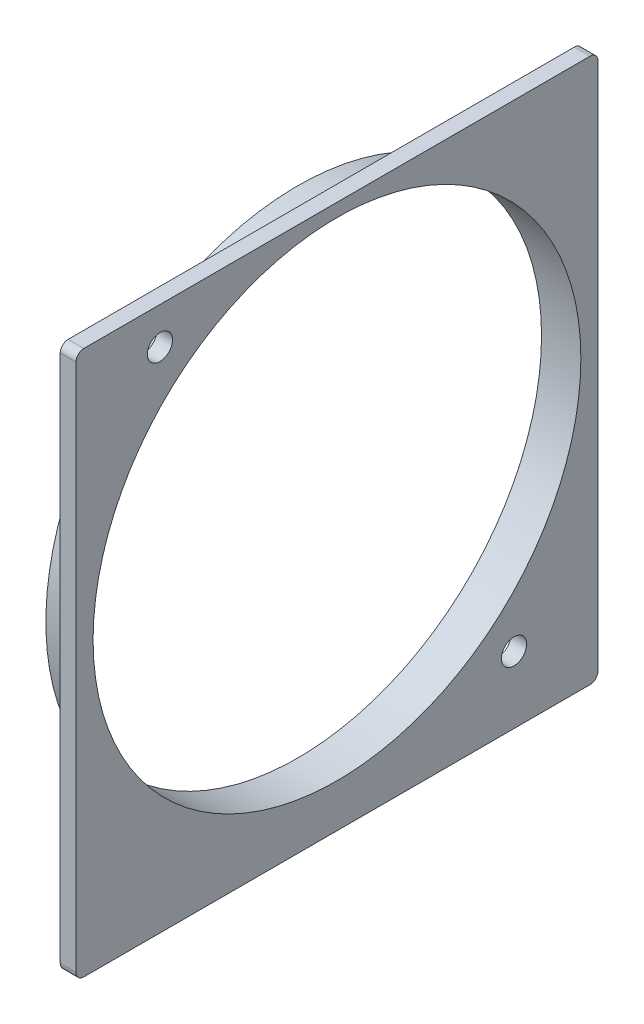
SolidWorks part; units mm, degrees
ref_plane "Front Plane" through (0, 0, 0) normal (0, 0, 1) x (1, 0, 0)
ref_plane "Top Plane" through (0, 0, 0) normal (0, 1, 0) x (1, 0, 0)
ref_plane "Right Plane" through (0, 0, 0) normal (1, 0, 0) x (0, 0, -1)
sketch "Sketch1" plane through (0, 0, 0) normal (1, 0, 0) x (0, 0, -1)
  line L1 (-33.175, -34.59) -> (33.175, -34.59)
  line L2 (-33.175, -34.59) -> (-33.175, 34.59)
  line L3 (-33.175, 34.59) -> (33.175, 34.59)
  line L4 (33.175, -34.59) -> (33.175, 34.59)
  line L5 (-33.175, -34.59) -> (33.175, 34.59) construction
  line L6 (-33.175, 34.59) -> (33.175, -34.59) construction
  point P0 (0, 0)
  dimension "D1" = 66.35
  dimension "D2" = 69.18
extrude "Boss-Extrude1" add sketch "Sketch1" along normal blind 2
sketch "Sketch2" plane through (0, 0, 0) normal (-1, 0, 0) x (0, 0, 1)
  line L0 (33.175, -34.59) -> (-33.175, -34.59) construction
  circle A0 centre (0, 1.91) radius 31
  dimension "D1" = 62
  dimension "D2" = 36.5
extrude "Cut-Extrude1" cut sketch "Sketch2" against normal through all
sketch "Sketch3" plane through (2, 0, 0) normal (1, 0, 0) x (0, 0, -1)
  line L1 (-22.5, -26.09) -> (22.5, -26.09) construction
  line L2 (-22.5, -26.09) -> (-22.5, 29.91) construction
  line L3 (-22.5, 29.91) -> (22.5, 29.91) construction
  line L4 (22.5, -26.09) -> (22.5, 29.91) construction
  line L5 (-22.5, -26.09) -> (22.5, 29.91) construction
  line L6 (-22.5, 29.91) -> (22.5, -26.09) construction
  point P0 (0, 1.91)
  dimension "D1" = 28
  dimension "D2" = 45
hole_wizard "M3 Clearance Hole1" positions "Sketch4" profile "Sketch5" hole size "M3" standard "ANSI Metric" end condition through all
sketch "Sketch4" plane through (2, 0, 0) normal (1, 0, 0) x (0, 0, -1)
  point P0 (-22.5, 29.91)
  point P3 (22.5, -26.09)
sketch "Sketch5" plane through (2, 29.91, 22.5) normal (0, 1, 0) x (0, 0, -1)
  line L0 (0, 0) -> (0, 2)
  line L1 (0, 2) -> (1.6, 2)
  line L2 (1.6, 2) -> (1.6, 0)
  line L5 (1.6, 0) -> (0, 0)
  line L11 (0, -6.35) -> (0, 107.95) construction
  dimension "Thru Hole Dia." = 3.2
  dimension "Thru Hole Depth" = 2
sketch "Sketch6" plane through (0, 0, 0) normal (1, 0, 0) x (0, 0, -1)
  circle A0 centre (0, 1.91) radius 31 construction
  circle A1 centre (0, 1.91) radius 31
  circle A2 centre (0, 1.91) radius 32
  dimension "D1" = 64
extrude "Boss-Extrude2" add sketch "Sketch6" against normal blind 3
fillet "Fillet1" radius 1 4 edges at (1, -34.59, -33.175) (1, -34.59, 33.175) (1, 34.59, -33.175) (1, 34.59, 33.175)
